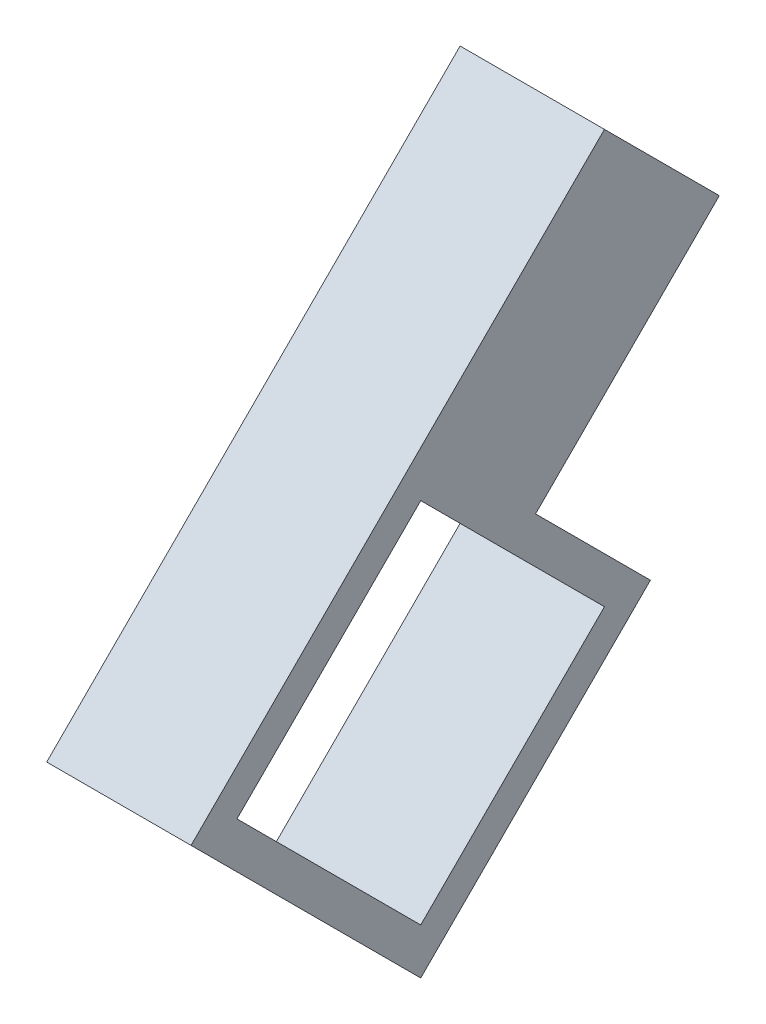
SolidWorks part; units mm, degrees
ref_plane "前视基准面" through (0, 0, 0) normal (0, 0, 1) x (1, 0, 0)
ref_plane "上视基准面" through (0, 0, 0) normal (0, 1, 0) x (1, 0, 0)
ref_plane "右视基准面" through (0, 0, 0) normal (1, 0, 0) x (0, 0, -1)
sketch "草图2" plane through (0, 0, 0) normal (1, 0, 0) x (0, 0, -1)
  line L4 (0, -31.8198) -> (31.8198, 0)
  line L5 (0, -31.8198) -> (-31.8198, 0)
  line L6 (31.8198, 0) -> (15.9099, 15.9099)
  line L7 (-31.8198, 0) -> (-15.9099, 15.9099)
  line L8 (-15.9099, 15.9099) -> (25.4558, 57.2756)
  line L9 (25.4558, 57.2756) -> (41.3657, 41.3657)
  line L10 (41.3657, 41.3657) -> (15.9099, 15.9099)
  dimension "D1" = 45
  dimension "D2" = 22.5
  dimension "D3" = 90
  dimension "D4" = 81
extrude "凸台-拉伸1" add sketch "草图2" along normal blind 20
sketch "草图3" plane through (20, 0, 0) normal (1, 0, 0) x (0, 0, -1)
  line L0 (0, -25.4558) -> (25.4558, 0)
  line L1 (0, -25.4558) -> (-25.4558, 0)
  line L2 (25.4558, 0) -> (0, 25.4558)
  line L3 (-25.4558, 0) -> (0, 25.4558)
  dimension "D1" = 36
extrude "切除-拉伸1" cut sketch "草图3" against normal blind 20
